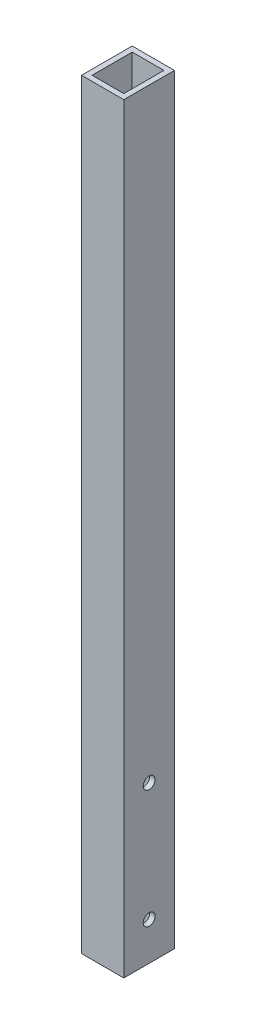
SolidWorks part; units mm, degrees
material "AISI 304"
ref_plane "Front Plane" through (0, 0, 0) normal (0, 0, 1) x (1, 0, 0)
ref_plane "Top Plane" through (0, 0, 0) normal (0, 1, 0) x (1, 0, 0)
ref_plane "Right Plane" through (0, 0, 0) normal (1, 0, 0) x (0, 0, -1)
sketch "Sketch1" plane through (0, 0, 0) normal (0, 1, 0) x (1, 0, 0)
  line L1 (31.75, -38.1) -> (-31.75, -38.1)
  line L2 (31.75, -38.1) -> (31.75, 38.1)
  line L3 (31.75, 38.1) -> (-31.75, 38.1)
  line L4 (-31.75, -38.1) -> (-31.75, 38.1)
  line L5 (31.75, -38.1) -> (-31.75, 38.1) construction
  line L6 (31.75, 38.1) -> (-31.75, -38.1) construction
  point P0 (0, 0)
  dimension "D1" = 63.5
  dimension "D2" = 76.2
extrude "Boss-Extrude1" add sketch "Sketch1" against normal blind 1143
sketch "Sketch2" plane through (0, -1143, 0) normal (0, -1, 0) x (1, 0, 0)
  line L0 (-31.75, 38.1) -> (31.75, 38.1) construction
  line L1 (-23.8125, 30.1625) -> (23.8125, 30.1625)
  line L2 (-23.8125, 30.1625) -> (-23.8125, -30.1625)
  line L3 (-23.8125, -30.1625) -> (23.8125, -30.1625)
  line L4 (23.8125, 30.1625) -> (23.8125, -30.1625)
  line L5 (-23.8125, 30.1625) -> (23.8125, -30.1625) construction
  line L6 (-23.8125, -30.1625) -> (23.8125, 30.1625) construction
  line L7 (31.75, 38.1) -> (31.75, -38.1) construction
  point P0 (0, 0)
  dimension "D1" = 7.9375
  dimension "D2" = 7.9375
extrude "Cut-Extrude1" cut sketch "Sketch2" against normal through all
sketch "Sketch3" plane through (-31.75, 0, 0) normal (-1, 0, 0) x (0, 0, 1)
  line L0 (-38.1, -1143) -> (38.1, -1143) construction
  line L1 (101.0497, -819.15) -> (-106.1196, -819.15) construction
  line L2 (38.1, -1143) -> (38.1, 0) construction
  circle A0 centre (0, -908.05) radius 8.89
  circle A1 centre (0, -1085.85) radius 8.89
  dimension "D4" = 17.78
  dimension "D5" = 17.78
  dimension "D1" = 38.1
  dimension "D2" = 177.8
  dimension "D3" = 323.85
  dimension "D6" = 88.9
  dimension "D7" = 38.1
extrude "Cut-Extrude2" cut sketch "Sketch3" against normal through all
